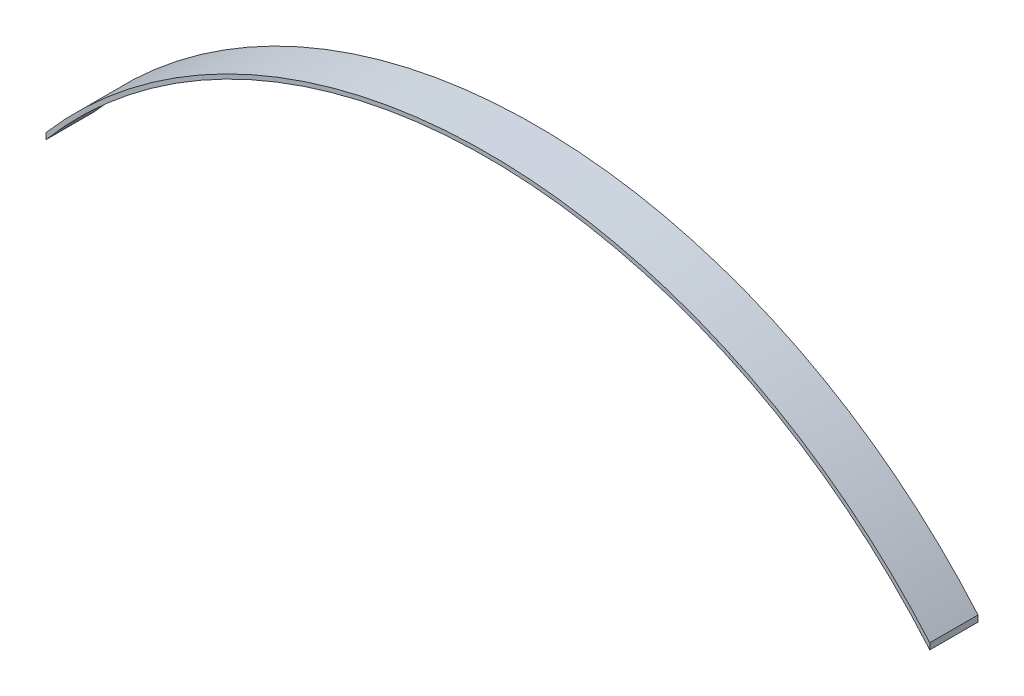
SolidWorks part; units mm, degrees
ref_plane "Face" through (0, 0, 0) normal (0, 0, 1) x (1, 0, 0)
ref_plane "Dessus" through (0, 0, 0) normal (0, 1, 0) x (1, 0, 0)
ref_plane "Droite" through (0, 0, 0) normal (1, 0, 0) x (0, 0, -1)
sketch "Esquisse2" plane through (0, 0, 0) normal (0, 0, 1) x (1, 0, 0)
  line L2 (-110, 94.4722) -> (-110, 92.9301)
  line L4 (110, 94.4722) -> (110, 92.9301)
  arc A0 (110, 94.4722) -> (-110, 94.4722) centre (0, 0) ccw
  arc A1 (110, 92.9301) -> (-110, 92.9301) centre (0, 0) ccw
  circle A3 centre (0, 0) radius 145 construction
  circle A4 centre (0, 0) radius 144 construction
  point P1 (143, 0)
  point P9 (138.6642, 42.3939)
  dimension "D1" = 290
  dimension "D3" = 110
  dimension "D4" = 110
  dimension "D2" = 1
extrude "Boss.-Extru.1" add sketch "Esquisse2" along normal blind 12
